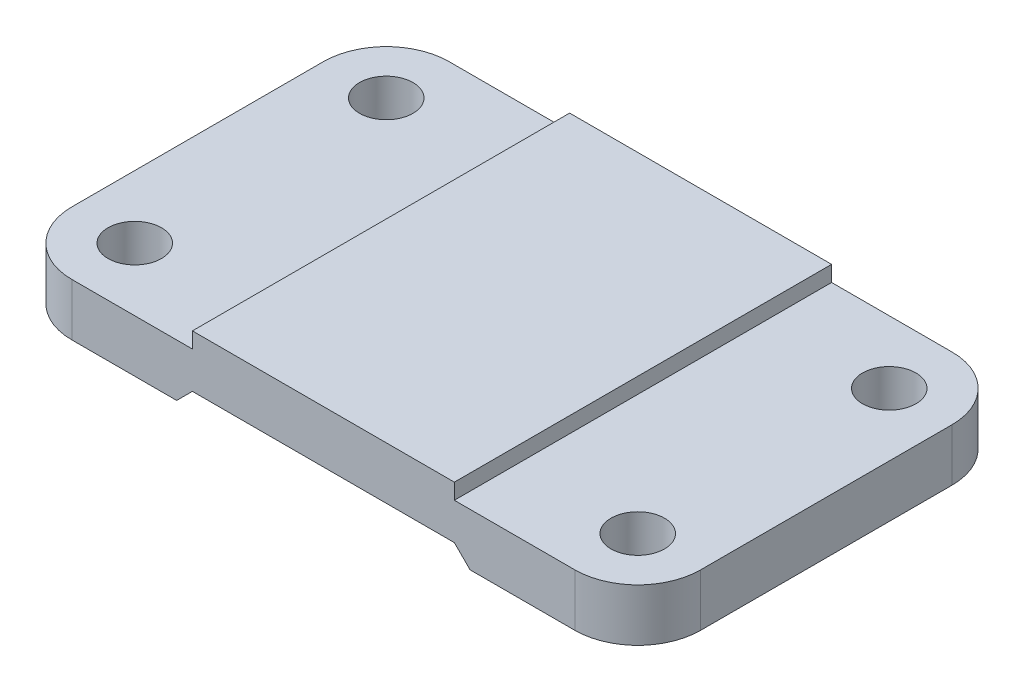
SolidWorks part; units mm, degrees
ref_plane "Front Plane" through (0, 0, 0) normal (0, 0, 1) x (1, 0, 0)
ref_plane "Top Plane" through (0, 0, 0) normal (0, 1, 0) x (1, 0, 0)
ref_plane "Right Plane" through (0, 0, 0) normal (1, 0, 0) x (0, 0, -1)
sketch "Sketch1" plane through (0, 0, 0) normal (0, 0, 1) x (1, 0, 0)
  line L0 (-25, 6.5) -> (-25, 3.5)
  line L1 (-60, -6.5) -> (-28, -6.5)
  line L2 (-60, -6.5) -> (-60, 3.5)
  line L3 (-25, 6.5) -> (25, 6.5)
  line L4 (60, -6.5) -> (60, 3.5)
  line L5 (0, 0) -> (14.1718, 0) construction
  line L7 (-25, 3.5) -> (25, 3.5)
  line L8 (25, 3.5) -> (25, 6.5)
  line L9 (0, 0) -> (0, -15.1179) construction
  line L10 (-28, -6.5) -> (-25, -3.5)
  line L11 (-25, -3.5) -> (25, -3.5)
  line L12 (25, -3.5) -> (28, -6.5)
  line L13 (28, -6.5) -> (60, -6.5)
  line L14 (25, 3.5) -> (60, 3.5)
  line L15 (-25, 3.5) -> (-60, 3.5)
  point P0 (0, 0)
  point P14 (0, -3.5)
  dimension "D1" = 120
  dimension "D2" = 13
  dimension "D3" = 50
  dimension "D4" = 3
  dimension "D5" = 45
  dimension "D6" = 56
  dimension "D7" = 3
extrude "Boss-Extrude2" add sketch "Sketch1" along normal blind 72 contours L7 L15 L2 L1 L10 L11 L12 L13 L4 L14 | L7 L8 L3 L0
hole_wizard "M12 Tapped Hole1" positions "Sketch3" profile "Sketch4" tap size "M12" standard "ISO"
sketch "Sketch3" plane through (0, 3.5, 0) normal (0, 1, 0) x (1, 0, 0)
  line L0 (0, 0) -> (0, -72) construction
  line L1 (-25, -72) -> (25, -72) construction
  line L3 (0, -36) -> (32.2328, -36) construction
  point P0 (-48, -12)
  point P2 (-48, -60)
  point P4 (48, -60)
  point P6 (48, -12)
  point P21 (0, 0)
  point P22 (0, 0)
  dimension "D1" = 48
  dimension "D2" = 96
sketch "Sketch4" plane through (-48, 3.5, 12) normal (1, 0, 0) x (0, 0, 1)
  line L0 (0, 0) -> (0, 29.25)
  line L1 (0, 29.25) -> (5.1, 29.25)
  line L2 (5.1, 29.25) -> (5.1, 0)
  line L5 (5.1, 0) -> (0, 0)
  line L10 (0, 29.25) -> (-5.1, 29.25) construction
  line L11 (0, -6.35) -> (0, 107.95) construction
  dimension "Tap Drill Dia." = 10.2
  dimension "Tap Drill Depth" = 29.25
  dimension "Drill Angle" = 180
cosmetic thread "Hole Thread1" parameters "D1"=24, "D2"=12
cosmetic thread "Hole Thread2" parameters "D1"=24, "D2"=12
cosmetic thread "Hole Thread3" parameters "D1"=24, "D2"=12
cosmetic thread "Hole Thread4" parameters "D1"=24, "D2"=12
fillet "Fillet1" radius 12 4 edges at (-60, -1.5, 0) (60, -1.5, 0) (-60, -1.5, 72) (60, -1.5, 72)
